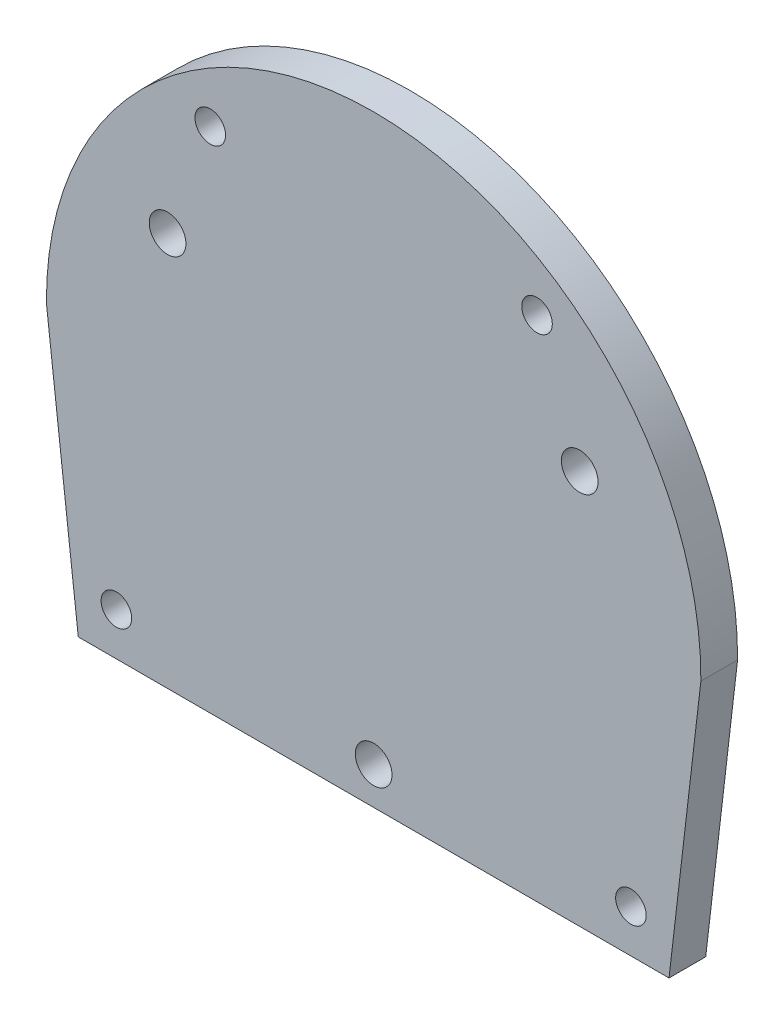
SolidWorks part; units mm, degrees
material "PLA"
ref_plane "Front" through (0, 0, 0) normal (0, 0, 1) x (1, 0, 0)
ref_plane "Top" through (0, 0, 0) normal (0, 1, 0) x (1, 0, 0)
ref_plane "Right" through (0, 0, 0) normal (1, 0, 0) x (0, 0, -1)
other "Configuration Table"
sketch "Esquisse1" plane through (0, 0, 0) normal (0, 0, 1) x (1, 0, 0)
  line L0 (-26.7494, -0.1796) -> (-24.1453, -22.5) construction
  line L1 (-26.7494, -0.1796) -> (-24.1453, -22.5)
  line L2 (26.7494, -0.1796) -> (24.1453, -22.5) construction
  line L3 (26.7494, -0.1796) -> (24.1453, -22.5)
  line L4 (-24.1453, -22.5) -> (24.1453, -22.5)
  line L5 (0, -19.45) -> (0, 0) construction
  line L6 (0, 0) -> (-16.8442, 9.725) construction
  line L7 (0, 0) -> (16.8442, 9.725) construction
  circle A0 centre (0, 0) radius 26.75
  circle A1 centre (0, 0) radius 19.45
  circle A2 centre (0, -19.45) radius 1.5
  circle A3 centre (16.8442, 9.725) radius 1.5
  circle A4 centre (-16.8442, 9.725) radius 1.5
  dimension "D1" = 38.9
  dimension "D3" = 3
  dimension "D5" = 120
  dimension "D6" = 120
extrude "Boss.-Extru.1" add sketch "Esquisse1" along normal blind 3 contours L1 A0 L4 L3 A4 A1 A3 A2 | A4 A1 A2 A3 | A0 L1 L4 | A0 L4 L3
sketch "Esquisse2" plane through (0, 0, 3) normal (0, 0, 1) x (1, 0, 0)
  circle A0 centre (21.0298, -19.0013) radius 1.25
  circle A1 centre (13.3548, 19.0318) radius 1.25
  circle A2 centre (-13.3548, 19.0318) radius 1.25
  circle A3 centre (-21.0298, -19.0013) radius 1.25
  circle A4 centre (21.0298, -19.0013) radius 1.25 construction
  circle A5 centre (-21.0298, -19.0013) radius 1.25 construction
  circle A6 centre (-13.3548, 19.0318) radius 1.25 construction
  circle A7 centre (13.3548, 19.0318) radius 1.25 construction
extrude "Enlèv. mat.-Extru.2" cut sketch "Esquisse2" against normal blind 10
